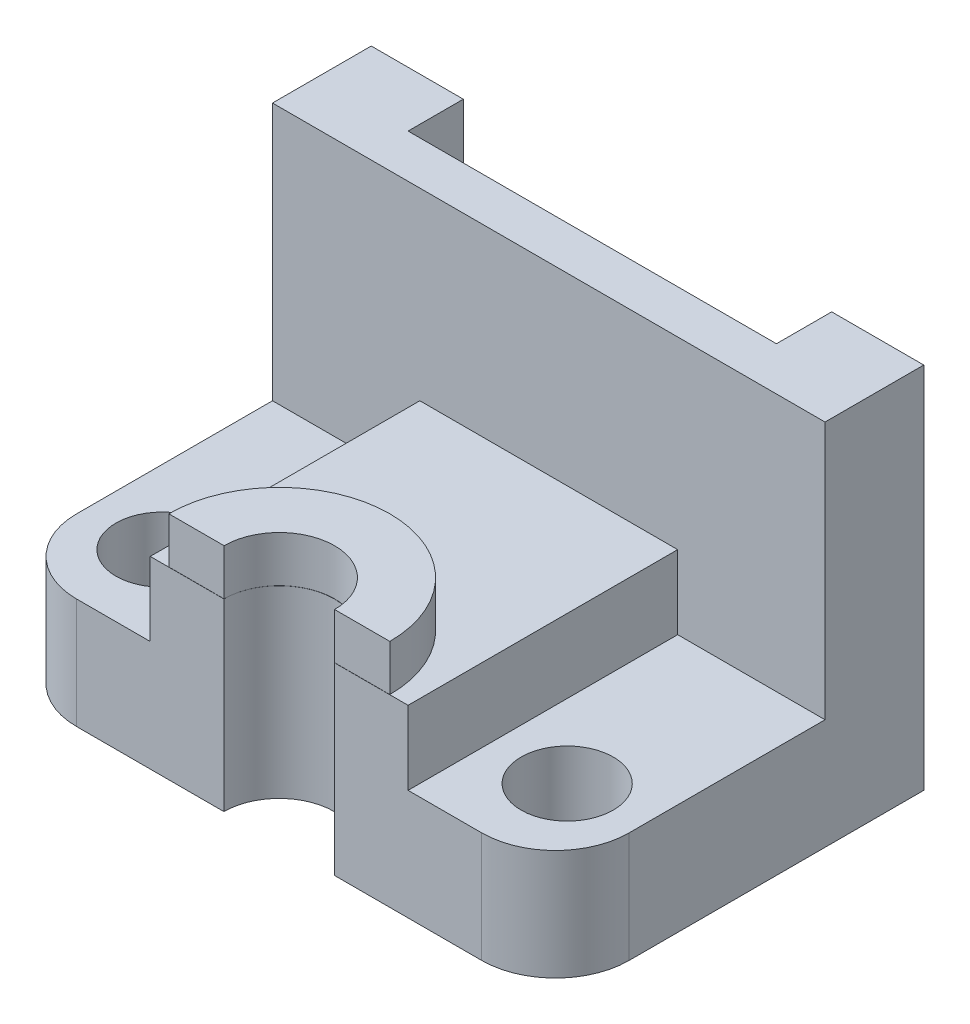
SolidWorks part; units mm, degrees
ref_plane "前视基准面" through (0, 0, 0) normal (0, 0, 1) x (1, 0, 0)
ref_plane "上视基准面" through (0, 0, 0) normal (0, 1, 0) x (1, 0, 0)
ref_plane "右视基准面" through (0, 0, 0) normal (1, 0, 0) x (0, 0, -1)
other "Configuration Table"
sketch "草图1" plane through (0, 0, 0) normal (0, 1, 0) x (1, 0, 0)
  line L1 (0, 0) -> (60, 0)
  line L2 (0, 0) -> (0, -40)
  line L3 (0, -40) -> (60, -40)
  line L4 (60, 0) -> (60, -40)
  dimension "D1" = 40
  dimension "D2" = 60
extrude "凸台-拉伸1" add sketch "草图1" along normal blind 40
sketch "草图2" plane through (0, 40, 0) normal (0, 1, 0) x (1, 0, 0)
  line L0 (60, 0) -> (0, 0) construction
  line L2 (10, 0) -> (50, 0)
  line L3 (60, -40) -> (60, 0) construction
  line L4 (50, 0) -> (50, -6)
  line L5 (50, -6) -> (10, -6)
  line L6 (10, -6) -> (10, 0)
  point P5 (30, 0)
  dimension "D1" = 30
  dimension "D2" = 40
extrude "切除-拉伸1" cut sketch "草图2" against normal through all
ref_plane "基准面1" through (30, 0, 0) normal (-1, 0, 0) x (0, 0, 1)
sketch "草图6" plane through (50, 0, 0) normal (-1, 0, 0) x (0, 0, 1)
  line L0 (10.7228, 40) -> (10.7228, 12)
  line L1 (0, 40) -> (40, 40) construction
  line L2 (10.7228, 12) -> (40, 12)
  line L3 (40, 40) -> (40, 0) construction
  line L4 (40, 12) -> (40, 40)
  line L5 (40, 40) -> (10.7228, 40)
  dimension "D1" = 28
extrude "切除-拉伸2" cut sketch "草图6" against normal through all both and the other way through all
sketch "草图7" plane through (0, 0, 40) normal (0, 0, 1) x (1, 0, 0)
  line L0 (16, 12) -> (44, 12)
  line L2 (60, 12) -> (0, 12) construction
  line L3 (16, 12) -> (16, 20)
  line L4 (16, 20) -> (44, 20)
  line L5 (44, 20) -> (44, 12)
  point P3 (30, 12)
extrude "凸台-拉伸2" add sketch "草图7" against normal up to next
sketch "草图8" plane through (0, 20, 0) normal (0, 1, 0) x (1, 0, 0)
  line L0 (30, 22) -> (30, -22) construction
  line L1 (18, -39.9809) -> (42, -39.9809)
  circle A0 centre (30, -39.9809) radius 6
  circle A1 centre (30, -39.9809) radius 12
  dimension "D1" = 12
  dimension "D2" = 24
extrude "凸台-拉伸4" add sketch "草图8" along normal blind 5 and the other way up to surface contours L1 A1 A0
sketch "草图11" plane through (0, 0, 40) normal (0, 0, 1) x (1, 0, 0)
  line L0 (8, 12) -> (52, 12)
  line L1 (16, 12) -> (0, 12) construction
  line L2 (30, 22) -> (30, -22) construction
  point P7 (30, 12)
  dimension "D1" = 22
sketch "草图12" plane through (0, 12, 0) normal (0, 1, 0) x (1, 0, 0)
  line L0 (8, -30.7228) -> (8, -40)
  line L1 (8, -40) -> (52, -40) construction
  line L2 (60, -10.7228) -> (0, -10.7228) construction
  line L3 (30, 22) -> (30, -22) construction
  circle A0 centre (8, -30.7228) radius 5
  circle A1 centre (52, -30.7228) radius 5
  dimension "D2" = 10
  dimension "D1" = 20
extrude "切除-拉伸4" cut sketch "草图12" against normal through all
fillet "圆角1" radius 8 2 edges at (60, 6, 40) (0, 6, 40)
sketch "草图14" plane through (0, 20, 0) normal (0, 1, 0) x (1, 0, 0)
  circle A0 centre (30, -40) radius 6
extrude "切除-拉伸5" cut sketch "草图14" against normal through all
